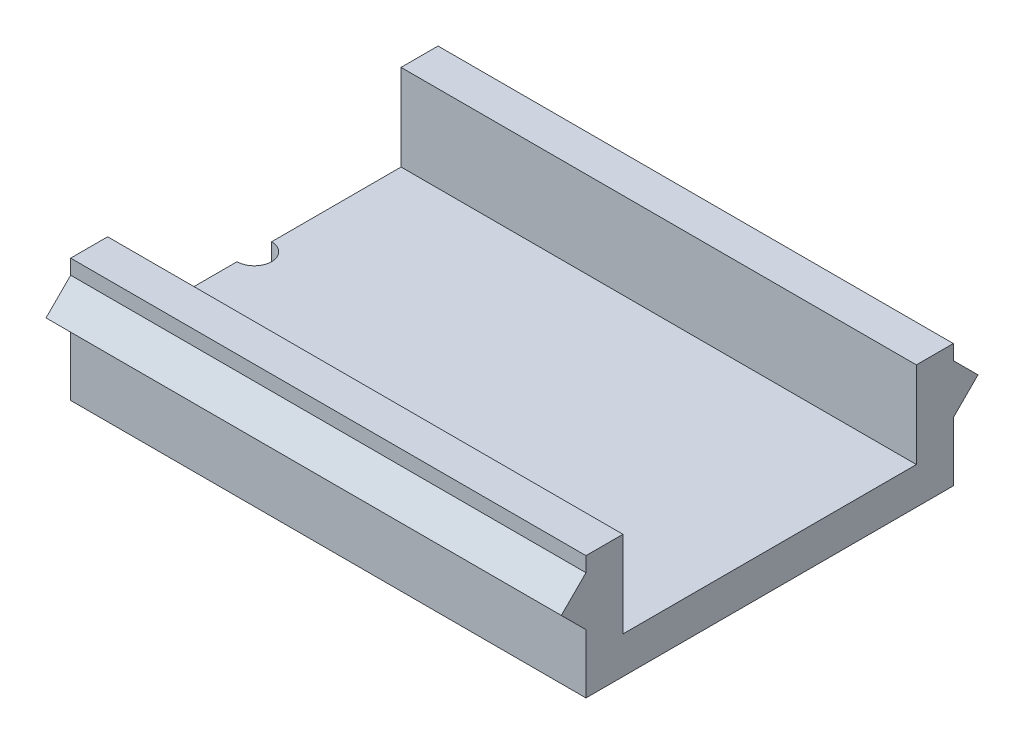
SolidWorks part; units mm, degrees
ref_plane "Спереди" through (0, 0, 0) normal (0, 0, 1) x (1, 0, 0)
ref_plane "Сверху" through (0, 0, 0) normal (0, 1, 0) x (1, 0, 0)
ref_plane "Справа" through (0, 0, 0) normal (1, 0, 0) x (0, 0, -1)
sketch "Sketch2" plane through (0, 0, 0) normal (0, 1, 0) x (1, 0, 0)
  line L0 (-20.9, 1.4) -> (-20.9, 14.9)
  line L1 (-20.9, -14.9) -> (20.9, -14.9)
  line L2 (-20.9, -14.9) -> (-20.9, -1.4)
  line L3 (-20.9, 14.9) -> (20.9, 14.9)
  line L4 (20.9, -14.9) -> (20.9, 14.9)
  line L5 (-20.9, -14.9) -> (20.9, 14.9) construction
  line L6 (-20.9, 14.9) -> (20.9, -14.9) construction
  line L7 (-20.9, 14.9) -> (-20.9, -14.9) construction
  arc A0 (-20.9, -1.4) -> (-20.9, 1.4) centre (-20.9, 0) ccw
  point P0 (0, 0)
  point P15 (-20.9, 0)
  dimension "D3" = 1.4
  dimension "D1" = 41.8
  dimension "D2" = 29.8
extrude "Boss-Extrude1" add sketch "Sketch2" along normal blind 3 contours L2 A0 L0 L3 L4 L1
sketch "Sketch4" plane through (-20.9, 0, 0) normal (-1, 0, 0) x (0, 0, 1)
  line L0 (-14.9, 3) -> (-14.9, 4.8)
  line L1 (-14.9, 4.8) -> (-16.9, 6.8)
  line L2 (-16.9, 6.8) -> (-14.9, 8.8)
  line L3 (-14.9, 8.8) -> (-14.9, 10)
  line L4 (-14.9, 10) -> (-11.9, 10)
  line L5 (-11.9, 10) -> (-11.9, 3)
  line L6 (14.9, 3) -> (1.4, 3) construction
  line L7 (0, 0) -> (0, 22.6198) construction
  line L8 (-14.9, 3) -> (-11.9, 3)
  line L9 (14.9, 0) -> (1.4, 0) construction
  line L10 (14.9, 3) -> (11.9, 3)
  line L11 (11.9, 10) -> (11.9, 3)
  line L12 (14.9, 10) -> (11.9, 10)
  line L13 (14.9, 8.8) -> (14.9, 10)
  line L14 (16.9, 6.8) -> (14.9, 8.8)
  line L15 (14.9, 4.8) -> (16.9, 6.8)
  line L16 (14.9, 3) -> (14.9, 4.8)
  line L17 (-1.4, 3) -> (1.4, 3) construction
  line L18 (-1.4, 3) -> (-14.9, 3) construction
  point P27 (0, 3)
  dimension "D1" = 2
  dimension "D2" = 45
  dimension "D3" = 10
  dimension "D4" = 1.2
  dimension "D5" = 3
extrude "Boss-Extrude2" add sketch "Sketch4" against normal up to surface (41.8 mm away) up to face at (20.9, 1.5, 0)
sketch "Sketch5" plane through (0, 0, 0) normal (0, -1, 0) x (1, 0, 0)
  circle A0 centre (0, 0) radius 2.6
  dimension "D1" = 5.2
extrude "Cut-Extrude1" cut sketch "Sketch5" against normal blind 0.6
